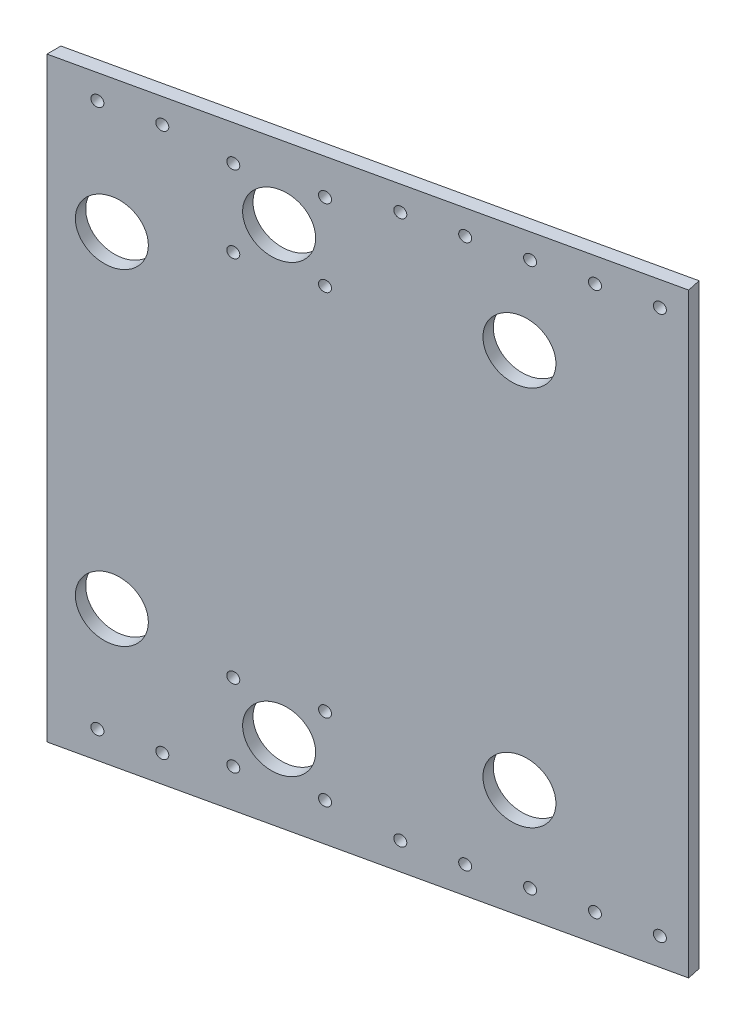
SolidWorks part; units mm, degrees
ref_plane "Front Plane" through (0, 0, 0) normal (0, 0, 1) x (1, 0, 0)
ref_plane "Top Plane" through (0, 0, 0) normal (0, 1, 0) x (1, 0, 0)
ref_plane "Right Plane" through (0, 0, 0) normal (1, 0, 0) x (0, 0, -1)
ref_plane "Plane1" through (158.2688, 0, 713.9043) normal (0.2164, 0, 0.9763) x (0, 1, 0)
sketch "Sketch1" plane through (158.2688, 0, 713.9043) normal (0.2164, 0, 0.9763) x (0, 1, 0)
  line L0 (284.48, -574.4213) -> (284.48, -323.2301)
  line L1 (284.48, -323.2301) -> (6.35, -323.2301)
  line L2 (6.35, -323.2301) -> (6.35, -574.4213)
  line L3 (6.35, -574.4213) -> (284.48, -574.4213)
extrude "Boss-Extrude1" add sketch "Sketch1" against normal blind 6.35
draft "Draft1" type of draft neutral plane draft angle 12.5 faces to draft 1 face at (473.1498, 145.415, 640.8448) neutral plane through (158.2688, 0, 713.9043) neutral plane normal (0.2164, 0, 0.9763) reverse direction yes parameters "D1"=12.5
hole_wizard "Hole1" positions "Sketch3" profile "Sketch2" legacy
sketch "Sketch3" plane through (158.2688, 0, 713.9043) normal (0.2164, 0, 0.9763) x (0.9763, 0, -0.2164)
  point P0 (348.6301, 69.85)
  point P1 (508.1661, 57.15)
  point P2 (508.1661, 234.95)
  point P3 (348.6301, 222.25)
  point P4 (414.1127, 42.0996)
  point P5 (414.1127, 250.0004)
sketch "Sketch2" plane through (498.6349, 69.85, 638.447) normal (0, 1, 0) x (0.9763, 0, -0.2164)
  line L0 (0, 0) -> (0, 59.1315)
  line L1 (0, 59.1315) -> (14.2875, 59.1315)
  line L2 (14.2875, 59.1315) -> (14.2875, 0)
  line L3 (14.2875, 0) -> (0, 0)
  line L4 (0, 110) -> (0, -10) construction
  dimension "Diameter" = 28.575
  dimension "Depth" = 59.1315
hole_wizard "#7 (0.201) Diameter Hole1" positions "Sketch5" profile "Sketch4" hole size "#7" standard "ANSI Inch"
sketch "Sketch5" plane through (158.2688, 0, 713.9043) normal (0.2164, 0, 0.9763) x (0.9763, 0, -0.2164)
  point P0 (461.5291, 273.05)
  point P1 (512.3291, 273.05)
  point P2 (563.1291, 273.05)
  point P3 (537.7291, 273.05)
  point P4 (486.9291, 273.05)
  point P5 (368.3689, 273.05)
  point P6 (461.5291, 19.05)
  point P7 (486.9291, 19.05)
  point P8 (512.3291, 19.05)
  point P9 (537.7291, 19.05)
  point P10 (563.1291, 19.05)
  point P11 (368.3689, 19.05)
  point P12 (342.9689, 19.05)
  point P13 (432.0732, 24.1391)
  point P14 (432.0732, 60.0601)
  point P15 (396.1521, 24.1391)
  point P16 (396.1521, 60.0601)
  point P17 (432.0732, 267.9609)
  point P18 (396.1521, 267.9609)
  point P19 (432.0732, 232.0399)
  point P20 (396.1521, 232.0399)
  point P21 (342.9689, 273.05)
sketch "Sketch4" plane through (608.8578, 273.05, 614.0111) normal (0, 1, 0) x (0.9763, 0, -0.2164)
  line L0 (0, 0) -> (0, 59.1315)
  line L1 (0, 59.1315) -> (2.5527, 59.1315)
  line L2 (2.5527, 59.1315) -> (2.5527, 0)
  line L5 (2.5527, 0) -> (0, 0)
  line L11 (0, -6.35) -> (0, 107.95) construction
  dimension "Thru Hole Dia." = 5.1054
  dimension "Thru Hole Depth" = 59.1315
